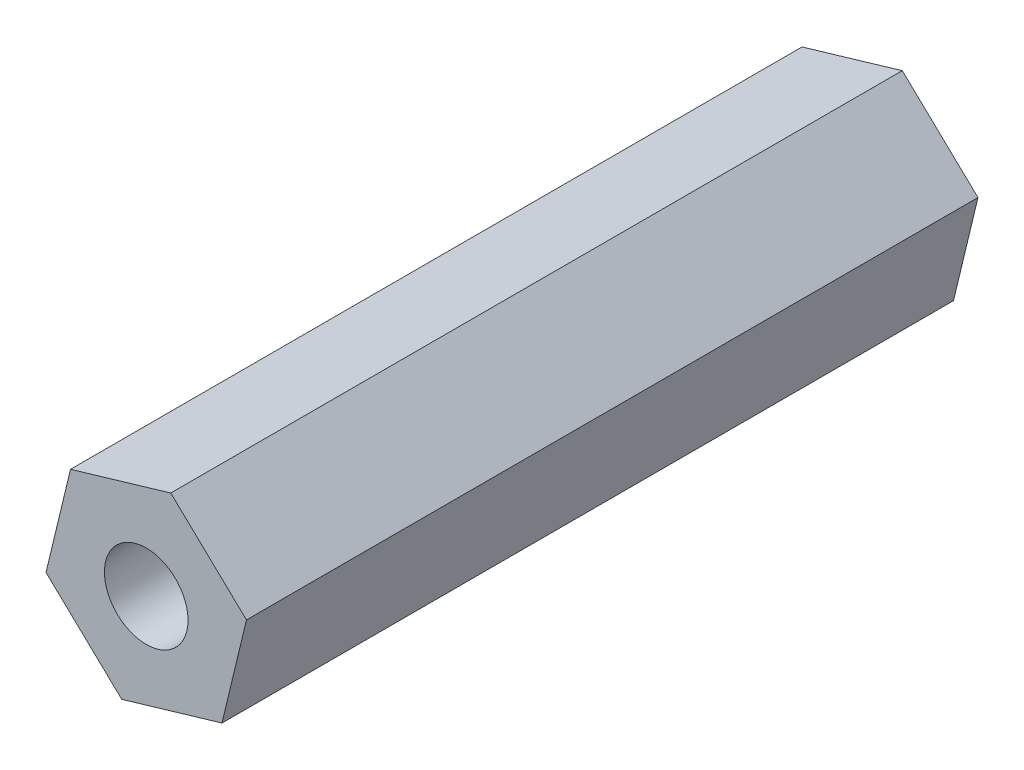
SolidWorks part; units mm, degrees
ref_plane "前视基准面" through (0, 0, 0) normal (0, 0, 1) x (1, 0, 0)
ref_plane "上视基准面" through (0, 0, 0) normal (0, 1, 0) x (1, 0, 0)
ref_plane "右视基准面" through (0, 0, 0) normal (1, 0, 0) x (0, 0, -1)
sketch "草图1" plane through (0, 0, 0) normal (0, 0, 1) x (1, 0, 0)
  line L1 (2.8985, -2.7566) -> (3.8365, 1.1319)
  line L2 (3.8365, 1.1319) -> (0.938, 3.8885)
  line L3 (0.938, 3.8885) -> (-2.8985, 2.7566)
  line L4 (-2.8985, 2.7566) -> (-3.8365, -1.1319)
  line L5 (-3.8365, -1.1319) -> (-0.938, -3.8885)
  line L6 (-0.938, -3.8885) -> (2.8985, -2.7566)
  circle A1 centre (0, 0) radius 3.4641 construction
extrude "凸台-拉伸1" add sketch "草图1" along normal blind 28
sketch "草图2" plane through (0, 0, 0) normal (0, 0, 1) x (1, 0, 0)
  circle A0 centre (0, 0) radius 1.6
extrude "切除-拉伸1" cut sketch "草图2" along normal blind 48
